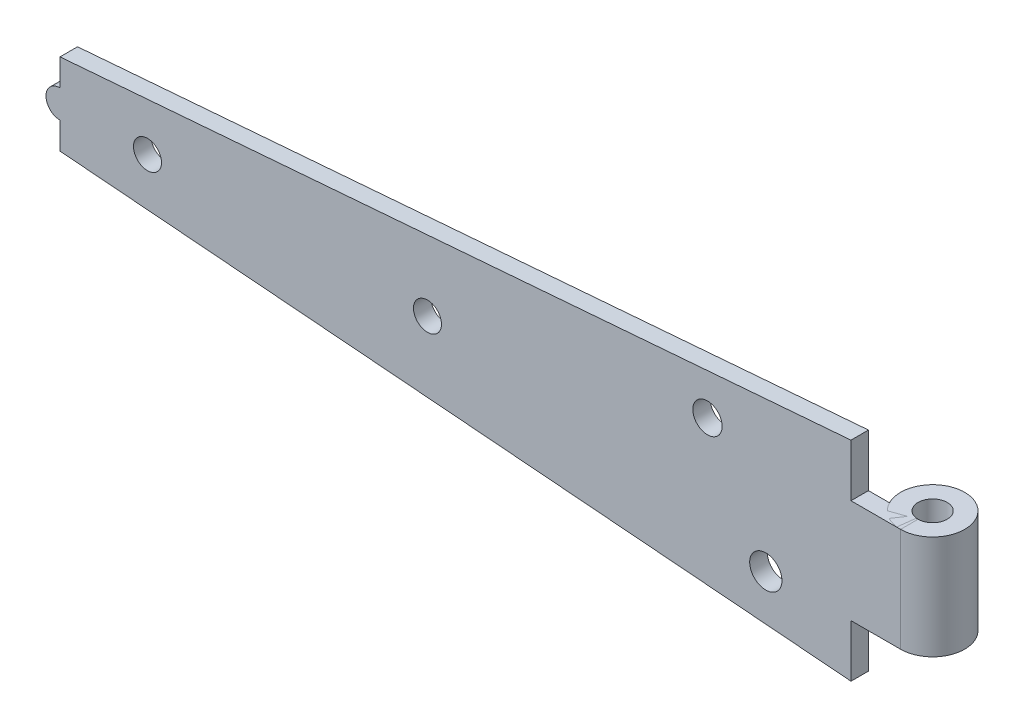
SolidWorks part; units mm, degrees
ref_plane "Front Plane" through (0, 0, 0) normal (0, 0, 1) x (1, 0, 0)
ref_plane "Top Plane" through (0, 0, 0) normal (0, 1, 0) x (1, 0, 0)
ref_plane "Right Plane" through (0, 0, 0) normal (1, 0, 0) x (0, 0, -1)
sketch "Sketch1" plane through (0, 0, 0) normal (0, 0, 1) x (1, 0, 0)
  line L0 (0, 0) -> (-135.6, 10.9)
  line L1 (-135.6, 10.9) -> (-135.6, 15.5)
  line L2 (-135.6, 24.9) -> (0, 35.8)
  line L3 (0, 35.8) -> (0, 26.8)
  line L4 (0, 0) -> (-135.6, 0) construction
  line L5 (-135.6, 0) -> (-135.6, 15.5) construction
  line L6 (-135.6, 35.8) -> (0, 35.8) construction
  line L7 (-24.6, 26.8) -> (-72.6, 17.9) construction
  line L8 (0, 26.8) -> (8.5, 26.8)
  line L10 (0, 9) -> (8.5, 9)
  line L11 (8.5, 26.8) -> (8.5, 9)
  line L12 (-135.6, 20.3) -> (-135.6, 24.9)
  line L13 (-135.6, 20.3) -> (-135.6, 35.8) construction
  line L14 (0, 9) -> (0, 0)
  arc A0 (-135.6, 20.3) -> (-135.6, 15.5) centre (-135.6, 17.9) ccw
  circle A1 centre (-120.6, 17.9) radius 2.4
  circle A2 centre (-72.6, 17.9) radius 2.4
  circle A3 centre (-24.6, 26.8) radius 2.515
  circle A4 centre (-14.6, 9) radius 2.764
  dimension "D4" = 4.8
  dimension "D5" = 4.8
  dimension "D6" = 4.8
  dimension "D1" = 10.9
  dimension "D2" = 10.9
  dimension "D3" = 14
  dimension "D7" = 135.6
  dimension "D8" = 8.5
  dimension "D9" = 9
  dimension "D10" = 9
  dimension "D11" = 15
  dimension "D12" = 48
  dimension "D13" = 48
  dimension "D14" = 10
  dimension "D15" = 9
  dimension "D16" = 9
extrude "Boss-Extrude1" add sketch "Sketch1" along normal blind 3
sketch "Sketch2" plane through (0, 0, 0) normal (0, 1, 0) x (1, 0, 0)
  line L0 (-138, 0) -> (-138, -3) construction
  line L1 (0, -3) -> (8.5, -3) construction
  circle A0 centre (8.5, 2.5) radius 5.5
  dimension "D1" = 146.5
  dimension "D2" = 11
  dimension "D3" = 5.5
extrude "Boss-Extrude2" add sketch "Sketch2" along normal blind 17.8 from offset 9 separate body
sketch "Sketch4" plane through (0, 0, 0) normal (0, 1, 0) x (1, 0, 0)
  circle A0 centre (8.5, 2.5) radius 2.5
  dimension "D1" = 5
extrude "Cut-Extrude1" cut sketch "Sketch4" along normal through all
